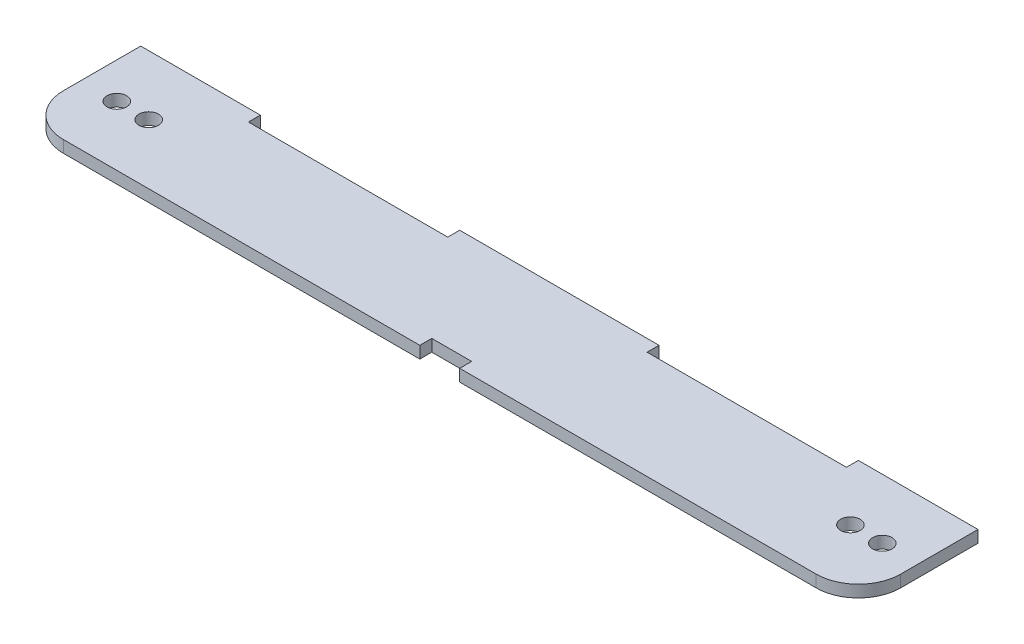
SolidWorks part; units mm, degrees
material "3mm Birch Ply Wood"
ref_plane "Front Plane" through (0, 0, 0) normal (0, 0, 1) x (1, 0, 0)
ref_plane "Top Plane" through (0, 0, 0) normal (0, 1, 0) x (1, 0, 0)
ref_plane "Right Plane" through (0, 0, 0) normal (1, 0, 0) x (0, 0, -1)
sketch "Sketch1" plane through (0, 0, 0) normal (0, 1, 0) x (1, 0, 0)
  line L1 (105, -15) -> (-105, -15)
  line L2 (105, -15) -> (105, 15)
  line L3 (105, 15) -> (-105, 15)
  line L4 (-105, -15) -> (-105, 15)
  line L5 (105, -15) -> (-105, 15) construction
  line L6 (105, 15) -> (-105, -15) construction
  point P0 (0, 0)
extrude "Boss-Extrude1" add sketch "Sketch1" along normal blind 3
sketch "Sketch2" plane through (0, 3, 0) normal (0, 1, 0) x (1, 0, 0)
  line L0 (-105, 15) -> (-75, 15) construction
  line L1 (105, 15) -> (-105, 15) construction
  line L2 (-25, 15) -> (25, 15) construction
  line L3 (-75, 15) -> (-25, 15)
  line L4 (-75, 15) -> (-75, 12)
  line L5 (-75, 12) -> (-25, 12)
  line L6 (-25, 15) -> (-25, 12)
  line L8 (25, 15) -> (75, 15)
  line L9 (25, 15) -> (25, 12)
  line L10 (25, 12) -> (75, 12)
  line L11 (75, 15) -> (75, 12)
extrude "Cut-Extrude1" cut sketch "Sketch2" against normal through all both and the other way through all
sketch "Sketch3" plane through (0, 0, 0) normal (0, -1, 0) x (1, 0, 0)
  line L0 (0, 15) -> (0, -15) construction
  line L2 (0, 15) -> (5, 15)
  line L3 (5, 15) -> (5, 12)
  line L4 (5, 12) -> (-5, 12)
  line L5 (-5, 12) -> (-5, 15)
  line L6 (-5, 15) -> (0, 15)
extrude "Cut-Extrude2" cut sketch "Sketch3" against normal through all both and the other way through all
sketch "Sketch5" plane through (0, 0, 0) normal (0, 1, 0) x (1, 0, 0)
  line L0 (-88, 0) -> (-96, 0) construction
  line L3 (-105, -15) -> (-92, -15) construction
  line L4 (-105, -15) -> (-5, -15) construction
  line L5 (-92, -15) -> (-92, 15) construction
  line L6 (-75, 15) -> (-105, 15) construction
  line L7 (0, 15) -> (0, -12) construction
  line L8 (25, 15) -> (-25, 15) construction
  line L9 (-5, -12) -> (5, -12) construction
  line L10 (92, -15) -> (92, 15) construction
  line L11 (105, -15) -> (92, -15) construction
  line L12 (88, 0) -> (96, 0) construction
  circle A0 centre (-96, 0) radius 2.45
  circle A1 centre (-88, 0) radius 2.45
  circle A2 centre (88, 0) radius 2.45
  circle A3 centre (96, 0) radius 2.45
  point P4 (-92, 0)
  point P27 (92, 0)
extrude "Cut-Extrude4" cut sketch "Sketch5" against normal through all and the other way through all
sketch "Sketch6" plane through (0, 0, 0) normal (0, 1, 0) x (1, 0, 0)
  line L0 (-105, -4.3934) -> (-105, -15)
  line L1 (-105, 15) -> (-105, -15) construction
  line L2 (-105, -15) -> (-5, -15) construction
  line L3 (-105, -15) -> (-94.3934, -15)
  line L4 (0, 15) -> (0, -20.554) construction
  line L5 (25, 15) -> (-25, 15) construction
  line L6 (105, -15) -> (94.3934, -15)
  line L7 (105, -4.3934) -> (105, -15)
  arc A0 (-105, -4.3934) -> (-94.3934, -15) centre (-94.3934, -4.3934) ccw
  arc A1 (105, -4.3934) -> (94.3934, -15) centre (94.3934, -4.3934) cw
extrude "Cut-Extrude5" cut sketch "Sketch6" against normal through all and the other way through all contours L0 L3 A0 | A1 L6 L7
